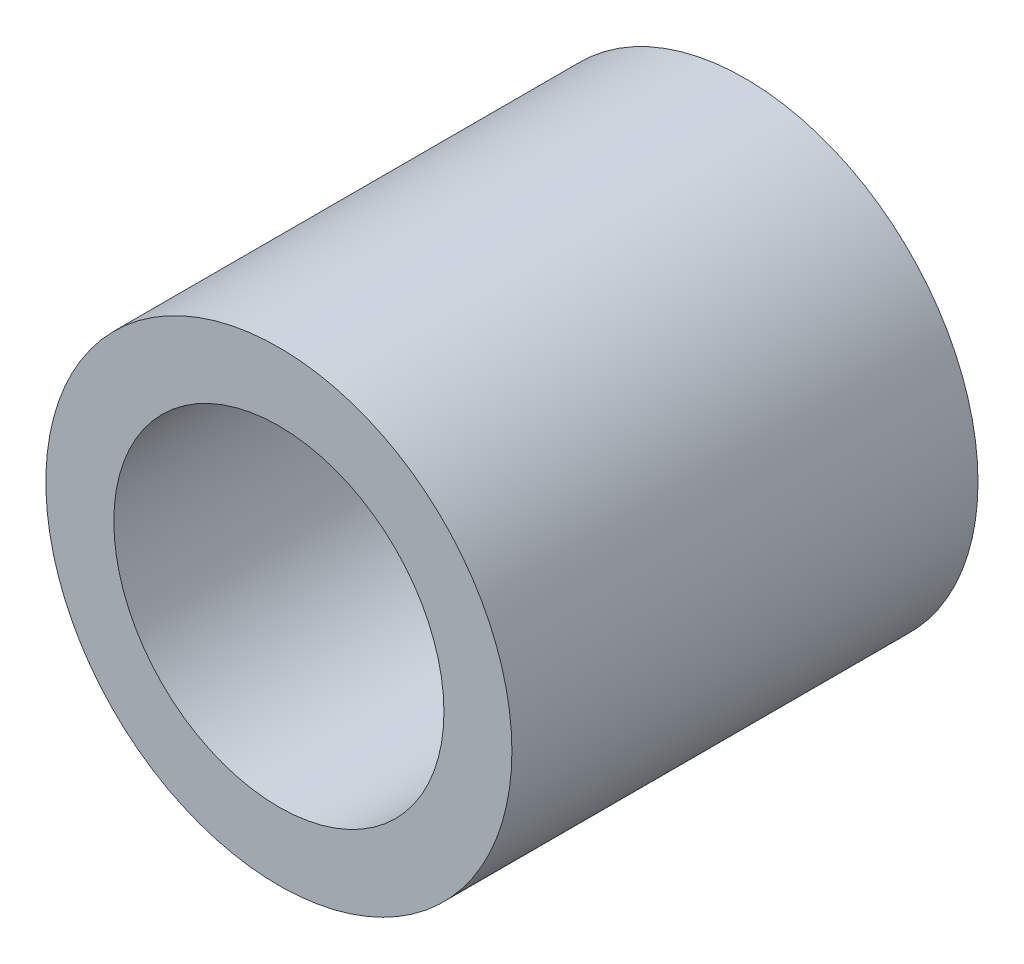
SolidWorks part; units mm, degrees
ref_plane "Front Plane" through (0, 0, 0) normal (0, 0, 1) x (1, 0, 0)
ref_plane "Top Plane" through (0, 0, 0) normal (0, 1, 0) x (1, 0, 0)
ref_plane "Right Plane" through (0, 0, 0) normal (1, 0, 0) x (0, 0, -1)
sketch "Sketch1" plane through (0, 0, 0) normal (0, 0, 1) x (1, 0, 0)
  circle A1 centre (-33, 0) radius 4.25
  circle A3 centre (-33, 0) radius 6
  dimension "D1" = 12
  dimension "D2" = 8.5
extrude "Boss-Extrude1" add sketch "Sketch1" along normal blind 12
